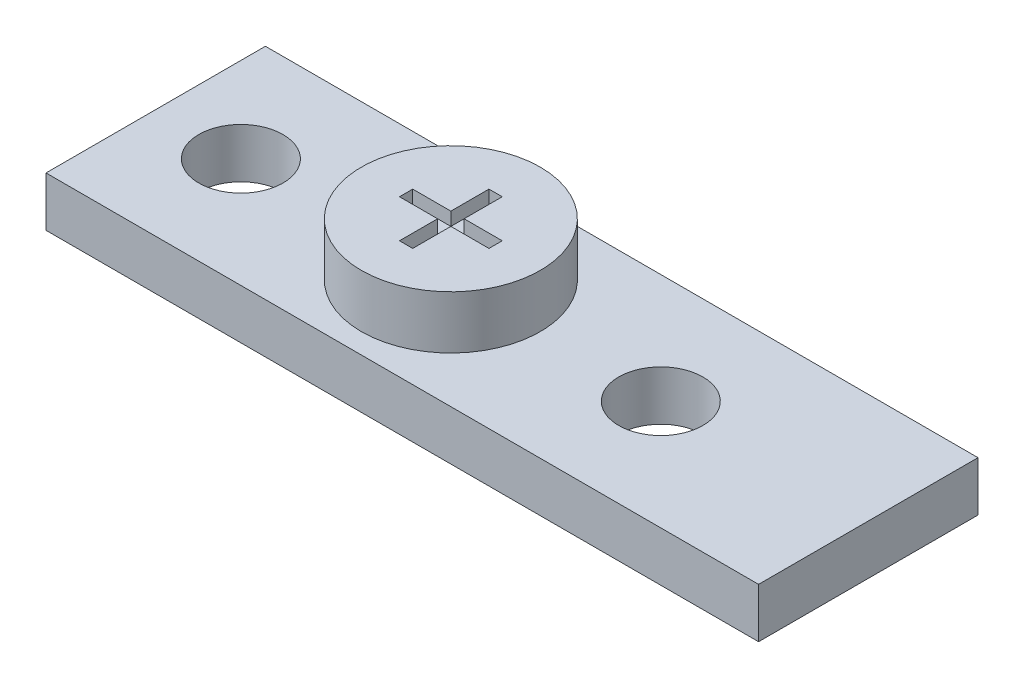
SolidWorks part; units mm, degrees
ref_plane "Front Plane" through (0, 0, 0) normal (0, 0, 1) x (1, 0, 0)
ref_plane "Top Plane" through (0, 0, 0) normal (0, 1, 0) x (1, 0, 0)
ref_plane "Right Plane" through (0, 0, 0) normal (1, 0, 0) x (0, 0, -1)
sketch "Sketch1" plane through (0, 0, 0) normal (0, 1, 0) x (1, 0, 0)
  line L0 (0, 4.2037) -> (27.305, 4.2037) construction
  line L1 (0, 0) -> (27.305, 0)
  line L2 (0, 0) -> (0, 8.4074)
  line L3 (0, 8.4074) -> (27.305, 8.4074)
  line L4 (27.305, 0) -> (27.305, 8.4074)
  circle A1 centre (3.2639, 4.2037) radius 1.6129
  circle A3 centre (19.3548, 4.2037) radius 1.6129
  point P14 (3.3089, 1.2017)
  dimension "D1" = 3.2258
  dimension "D2" = 3.2639
  dimension "D3" = 16.0909
  dimension "D4" = 8.4074
  dimension "D5" = 27.305
extrude "Base PCB" add sketch "Sketch1" along normal blind 1.905
sketch "Sketch2" plane through (0, 1.905, 0) normal (0, 1, 0) x (1, 0, 0)
  line L0 (4.8768, 4.2037) -> (17.7419, 4.2037) construction
  circle A0 centre (3.2639, 4.2037) radius 1.6129 construction
  circle A1 centre (19.3548, 4.2037) radius 1.6129 construction
  circle A2 centre (11.3093, 4.2037) radius 3.429
  dimension "D1" = 6.858
extrude "Screw Head (Unscrewed)" add sketch "Sketch2" along normal blind 2.032
sketch "Sketch3" plane through (0, 0, 0) normal (0, -1, 0) x (1, 0, 0)
  line L0 (4.8768, -4.2037) -> (17.7419, -4.2037) construction
  circle A0 centre (3.2639, -4.2037) radius 1.6129 construction
  circle A1 centre (19.3548, -4.2037) radius 1.6129 construction
  circle A2 centre (11.3093, -4.2037) radius 2.921
  dimension "D1" = 5.842
extrude "Threaded Hole Boss" add sketch "Sketch3" along normal blind 0.762
sketch "Sketch4" plane through (0, -0.762, 0) normal (0, -1, 0) x (1, 0, 0)
  circle A0 centre (11.3093, -4.2037) radius 1.397
  dimension "D1" = 2.794
extrude "Screw Stickout (Screwed)" add sketch "Sketch4" along normal blind 0.889
sketch "Sketch5" plane through (0, 3.937, 0) normal (0, 1, 0) x (1, 0, 0)
  line L1 (11.0554, 2.4892) -> (11.5633, 2.4892)
  line L2 (11.0554, 2.4892) -> (11.0554, 5.9182)
  line L3 (11.0554, 5.9182) -> (11.5633, 5.9182)
  line L4 (11.5633, 2.4892) -> (11.5633, 5.9182)
  line L5 (11.0554, 2.4892) -> (11.5633, 5.9182) construction
  line L6 (11.0554, 5.9182) -> (11.5633, 2.4892) construction
  line L7 (9.5948, 3.9497) -> (13.0238, 3.9497)
  line L8 (9.5948, 3.9497) -> (9.5948, 4.4577)
  line L9 (9.5948, 4.4577) -> (13.0238, 4.4577)
  line L10 (13.0238, 3.9497) -> (13.0238, 4.4577)
  line L11 (9.5948, 3.9497) -> (13.0238, 4.4577) construction
  line L12 (9.5948, 4.4577) -> (13.0238, 3.9497) construction
  point P0 (11.3093, 4.2037)
  point P1 (11.3094, 4.2037)
  dimension "D1" = 3.429
  dimension "D2" = 0.508
extrude "2s LiPo Mounting" cut sketch "Sketch5" against normal blind 0.508 contours L2 L9 L4 L3 | L9 L8 L7 L2 | L9 L2 L7 L4 | L7 L2 L1 L4 | L7 L10 L9 L4
